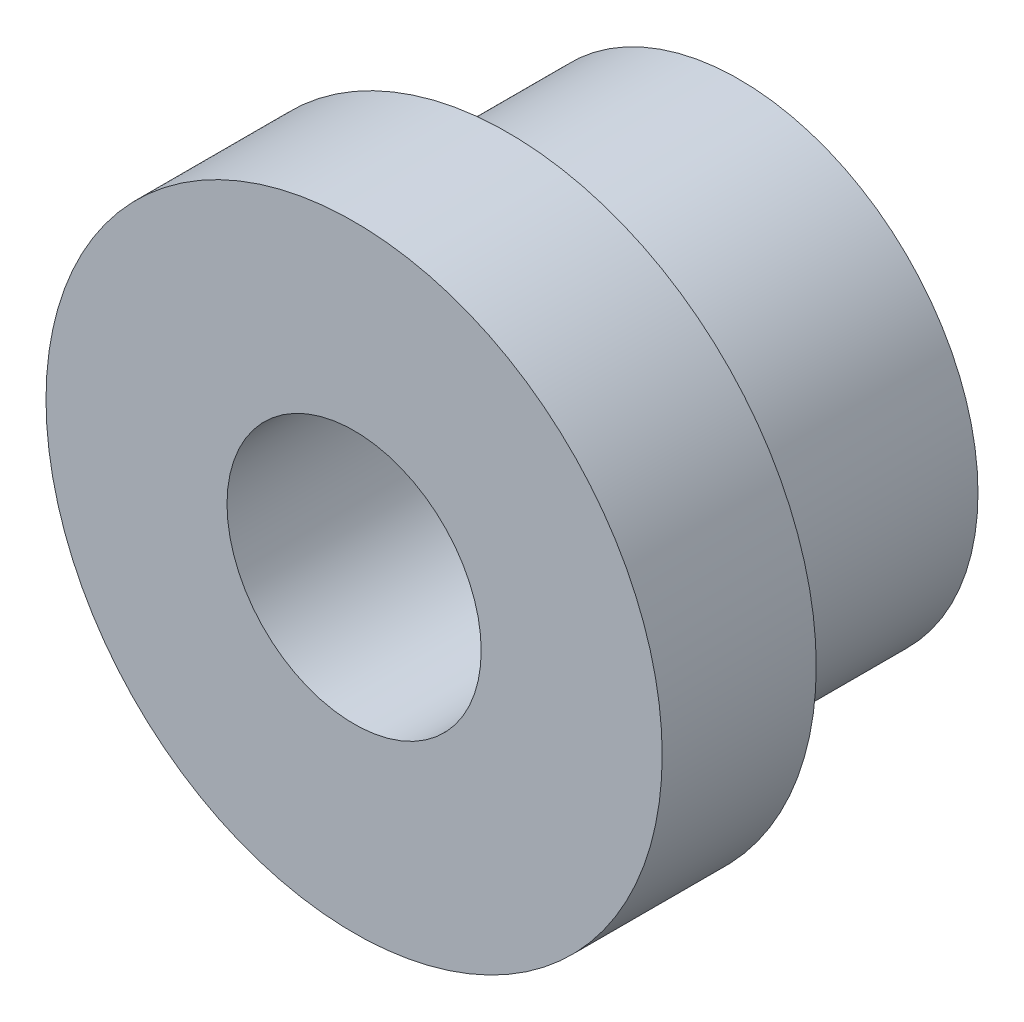
SolidWorks part; units mm, degrees
material "ABS"
ref_plane "前视基准面" through (0, 0, 0) normal (0, 0, 1) x (1, 0, 0)
ref_plane "上视基准面" through (0, 0, 0) normal (0, 1, 0) x (1, 0, 0)
ref_plane "右视基准面" through (0, 0, 0) normal (1, 0, 0) x (0, 0, -1)
sketch "草图1" plane through (0, 0, 0) normal (0, 0, 1) x (1, 0, 0)
  circle A0 centre (0, 0) radius 3.1
  circle A1 centre (0, 0) radius 1.65
  dimension "D1" = 6.2
  dimension "D2" = 3.3
extrude "凸台-拉伸1" add sketch "草图1" along normal blind 3
sketch "草图2" plane through (0, 0, 3) normal (0, 0, 1) x (1, 0, 0)
  circle A0 centre (0, 0) radius 1.65
  circle A1 centre (0, 0) radius 4
  dimension "D1" = 8
  dimension "D2" = 3.3
extrude "凸台-拉伸2" add sketch "草图2" along normal blind 2
